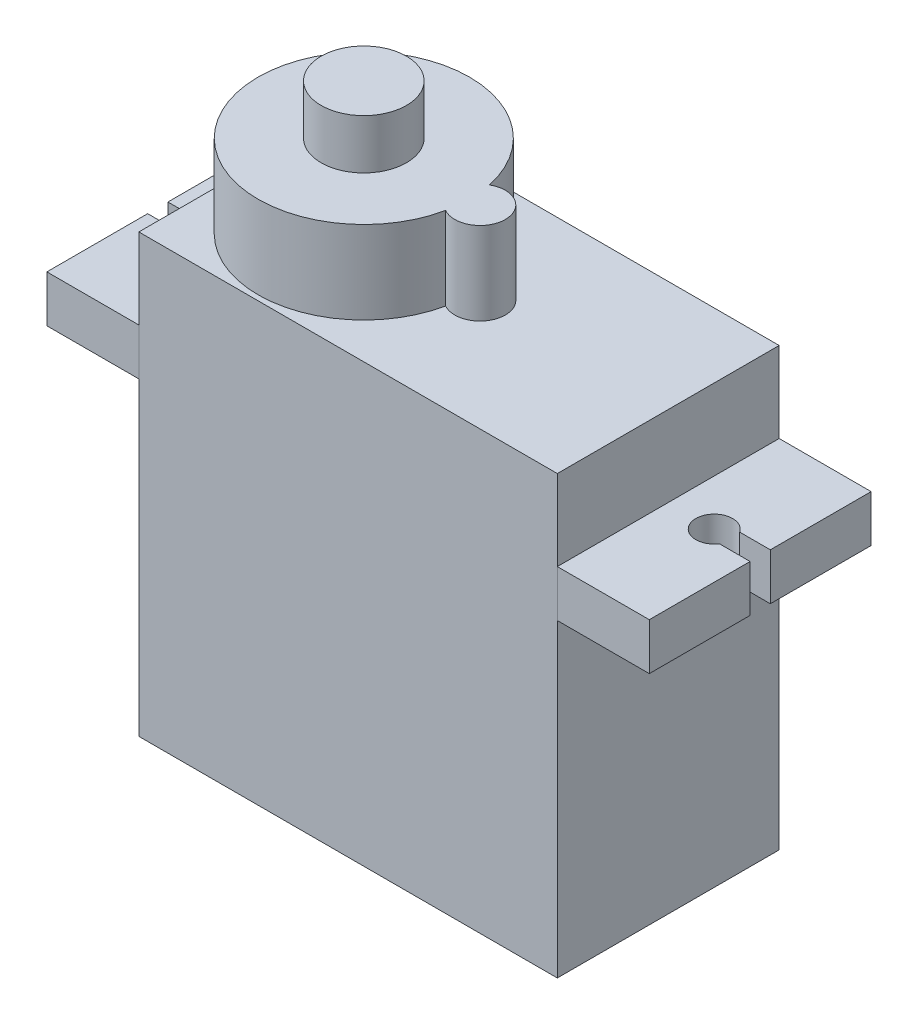
SolidWorks part; units mm, degrees
ref_plane "Front Plane" through (0, 0, 0) normal (0, 0, 1) x (1, 0, 0)
ref_plane "Top Plane" through (0, 0, 0) normal (0, 1, 0) x (1, 0, 0)
ref_plane "Right Plane" through (0, 0, 0) normal (1, 0, 0) x (0, 0, -1)
sketch "Sketch1" plane through (0, 0, 0) normal (0, 1, 0) x (1, 0, 0)
  line L1 (-11.375, -6.03) -> (11.375, -6.03)
  line L2 (-11.375, -6.03) -> (-11.375, 6.03)
  line L3 (-11.375, 6.03) -> (11.375, 6.03)
  line L4 (11.375, -6.03) -> (11.375, 6.03)
  line L5 (-11.375, -6.03) -> (11.375, 6.03) construction
  line L6 (-11.375, 6.03) -> (11.375, -6.03) construction
  point P0 (0, 0)
  dimension "D1" = 22.75
  dimension "D2" = 12.06
extrude "Boss-Extrude1" add sketch "Sketch1" along normal blind 23.75
sketch "Sketch2" plane through (11.375, 0, 0) normal (1, 0, 0) x (0, 0, -1)
  line L0 (-6.03, 23.75) -> (-6.03, 0) construction
  line L1 (-6.03, 19.37) -> (6.03, 19.37)
  line L2 (-6.03, 19.37) -> (-6.03, 16.83)
  line L3 (-6.03, 16.83) -> (6.03, 16.83)
  line L4 (6.03, 19.37) -> (6.03, 16.83)
  line L5 (6.03, 23.75) -> (6.03, 0) construction
  line L6 (-6.03, 23.75) -> (6.03, 23.75) construction
  dimension "D1" = 4.38
  dimension "D2" = 2.54
extrude "Boss-Extrude2" add sketch "Sketch2" along normal blind 5 separate body
sketch "Sketch3" plane through (-11.375, 0, 0) normal (-1, 0, 0) x (0, 0, 1)
  line L4 (6.03, 16.83) -> (6.03, 19.37)
  line L5 (-6.03, 16.83) -> (6.03, 16.83)
  line L6 (-6.03, 19.37) -> (-6.03, 16.83)
  line L7 (6.03, 19.37) -> (-6.03, 19.37)
  line L8 (6.03, 16.83) -> (6.03, 19.37)
  line L9 (-6.03, 16.83) -> (6.03, 16.83)
  line L10 (-6.03, 19.37) -> (-6.03, 16.83)
  line L11 (6.03, 19.37) -> (-6.03, 19.37)
  dimension "D1" = 0
extrude "Boss-Extrude3" add sketch "Sketch3" along normal blind 5 separate body
sketch "Sketch4" plane through (0, 19.37, 0) normal (0, 1, 0) x (1, 0, 0)
  line L0 (-16.375, -6.03) -> (-16.375, 6.03) construction
  line L1 (16.375, 6.03) -> (16.375, -6.03) construction
  line L3 (-16.375, 0.55) -> (-14.7102, 0.55)
  line L4 (-16.375, 0.55) -> (-16.375, -0.55)
  line L5 (-16.375, -0.55) -> (-14.7102, -0.55)
  line L7 (16.375, -0.55) -> (14.7102, -0.55)
  line L8 (16.375, -0.55) -> (16.375, 0.55)
  line L9 (16.375, 0.55) -> (14.7102, 0.55)
  arc A0 (-14.7102, -0.55) -> (-14.7102, 0.55) centre (-13.875, 0) ccw
  arc A1 (14.7102, 0.55) -> (14.7102, -0.55) centre (13.875, 0) ccw
  dimension "D1" = 2
  dimension "D2" = 2
  dimension "D4" = 2.5
  dimension "D3" = 2.5
  dimension "D5" = 1.1
  dimension "D6" = 0.55
  dimension "D7" = 1.1
  dimension "D8" = 0.55
extrude "Cut-Extrude1" cut sketch "Sketch4" against normal up to next (2.54 mm away)
sketch "Sketch5" plane through (0, 19.37, 0) normal (0, 1, 0) x (1, 0, 0)
  line L0 (16.375, 6.03) -> (16.375, -6.03) construction
  line L1 (14.7102, 0.55) -> (16.375, 0.55)
  line L3 (14.7102, -0.55) -> (16.375, -0.55)
  line L4 (16.375, 0.55) -> (16.375, -0.55)
  arc A0 (14.7102, 0.55) -> (14.7102, -0.55) centre (13.875, 0) ccw
  dimension "D1" = 2
  dimension "D2" = 1.1
  dimension "D3" = 0.55
  dimension "D4" = 2.5
extrude "Cut-Extrude2" cut sketch "Sketch5" against normal up to next (2.54 mm away) contours L1 L4 L3 A0
sketch "Sketch6" plane through (0, 23.75, 0) normal (0, 1, 0) x (1, 0, 0)
  line L0 (-11.375, 6.03) -> (-11.375, -6.03) construction
  line L1 (1.125, 1.3944) -> (0.4034, 1.3944)
  line L2 (1.125, -1.3556) -> (0.4129, -1.3556)
  arc A0 (0.4453, 1.2146) -> (0.4526, -1.18) centre (-5.175, 0) ccw
  arc A1 (0.4526, -1.18) -> (0.4453, 1.2146) centre (1.125, 0.0194) ccw
  dimension "D2" = 11.5
  dimension "D3" = 2.75
  dimension "D1" = 6.2
  dimension "D4" = 6.3
extrude "Boss-Extrude4" add sketch "Sketch6" along normal blind 4.5 contours A1 A0
sketch "Sketch7" plane through (0, 28.25, 0) normal (0, 1, 0) x (1, 0, 0)
  circle A0 centre (-5.175, 0) radius 2.32
  dimension "D1" = 4.64
extrude "Boss-Extrude5" add sketch "Sketch7" along normal blind 2.7
sketch "Sketch8" plane through (-11.375, 0, 0) normal (-1, 0, 0) x (0, 0, 1)
  line L0 (-6.03, 0) -> (6.03, 0) construction
  circle A0 centre (-1.2, 4.5) radius 0.6
  circle A1 centre (0, 4.5) radius 0.6
  circle A2 centre (1.2, 4.5) radius 0.6
  dimension "D1" = 4.5
  dimension "D2" = 1.2
  dimension "D3" = 1.2
  dimension "D4" = 1.2
extrude "Boss-Extrude7" add sketch "Sketch8" along normal blind 2.3 separate body contours A1 | A0 | A2
